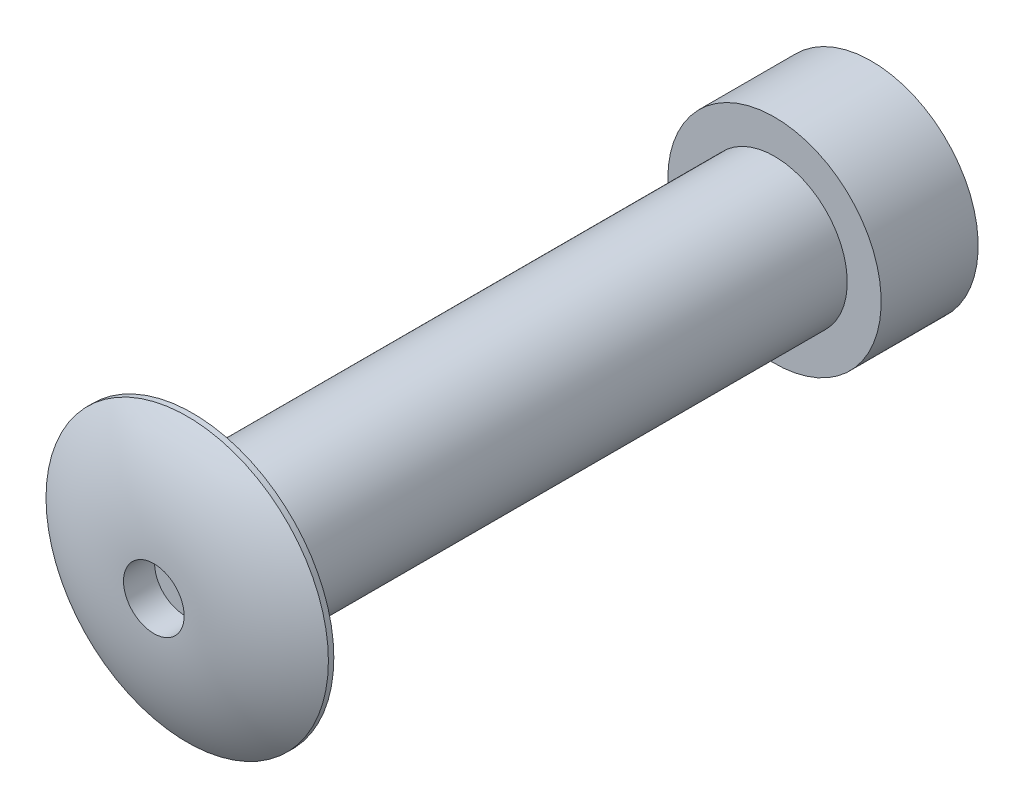
SolidWorks part; units mm, degrees
material "6061-T6 (SS)"
ref_plane "Front" through (0, 0, 0) normal (0, 0, 1) x (1, 0, 0)
ref_plane "Top" through (0, 0, 0) normal (0, 1, 0) x (1, 0, 0)
ref_plane "Right" through (0, 0, 0) normal (1, 0, 0) x (0, 0, -1)
sketch "layout" plane through (0, 0, 0) normal (1, 0, 0) x (0, 0, -1)
  line L0 (-29.845, 0) -> (-1.27, 0) construction
  line L1 (-1.27, 0) -> (0, 0) construction
  line L2 (0, 0) -> (19.05, 0) construction
  line L3 (19.05, 0) -> (20.955, 0) construction
  line L8 (0, 4.6228) -> (0, -4.6228) construction
  line L9 (19.05, 2.3813) -> (19.05, -2.3813) construction
  dimension "D5" = 1.905
sketch "Sketch2" plane through (0, 0, 0) normal (1, 0, 0) x (0, 0, -1)
  line L0 (-29.845, 0) -> (-29.845, 0.9922) construction
  line L1 (-1.27, 0.9922) -> (-1.27, 0)
  line L2 (19.05, 0) -> (-1.27, 0)
  line L3 (0, 0) -> (0, 4.6228) construction
  line L4 (-1.27, 0) -> (-1.27, -1.8472) construction
  line L5 (19.05, 2.3813) -> (0, 2.3812)
  line L7 (19.5263, 2.3813) -> (19.5263, -1.9844) construction
  line L8 (-1.27, 0) -> (19.05, 0) construction
  line L9 (20.955, 0) -> (20.955, 2.3813) construction
  line L10 (19.05, 2.3813) -> (19.5263, 2.3813) construction
  line L11 (19.5263, 2.3813) -> (20.0025, 2.3813) construction
  line L12 (-7.6006, 0) -> (-29.845, 0) construction
  line L13 (-1.27, 0.9922) -> (-1.27, 0) construction
  line L14 (20.0025, 2.3813) -> (20.4788, 2.3813) construction
  line L15 (20.4788, 2.3813) -> (20.955, 2.3813) construction
  line L16 (-1.27, 0) -> (19.05, 0) construction
  line L17 (19.05, 2.3813) -> (19.05, 3.4925)
  line L18 (19.5263, 0) -> (20.955, 0) construction
  line L19 (0, 2.3812) -> (0, 4.6228)
  line L20 (-1.27, 0.9922) -> (-29.845, 0.9922) construction
  line L21 (-29.845, 0) -> (-1.27, 0) construction
  line L22 (0, 4.6228) -> (-0.1778, 4.6228)
  line L23 (19.05, 0) -> (19.5263, 0) construction
  line L24 (19.05, 3.4925) -> (22.225, 3.4925)
  line L25 (22.225, 3.4925) -> (22.225, 0)
  line L26 (19.05, 0) -> (22.225, 0)
  arc A2 (-0.1778, 4.6228) -> (-1.27, 0.9922) centre (5.3104, 0.9922) ccw
  dimension "D1" = 0.1778
  dimension "D2" = 2.3813
  dimension "D3" = 0.9922
  dimension "D4" = 3.175
  dimension "D5" = 6.985
revolve "Revolve1" add sketch "Sketch2" angle 360 about L12
sketch "Sketch4" plane through (0, 0, 1.27) normal (0, 0, 1) x (1, 0, 0)
  circle A1 centre (0, 0) radius 0.9922 construction
  circle A2 centre (0, 0) radius 0.9922
extrude "Cut-Extrude1" cut sketch "Sketch4" against normal blind 1.016
sketch "Sketch3" plane through (0, 0, -22.225) normal (0, 0, -1) x (-1, 0, 0)
  circle A1 centre (0, 0) radius 0.9922 construction
  circle A2 centre (0, 0) radius 0.9922
extrude "Cut-Extrude2" cut sketch "Sketch3" against normal blind 2.54
other "Freeze***"
equation "\"D5@layout\"=\"Head Height@layout\"*1.5"
equation "\"D9@layout\"=\"length@layout\"*1.5"
